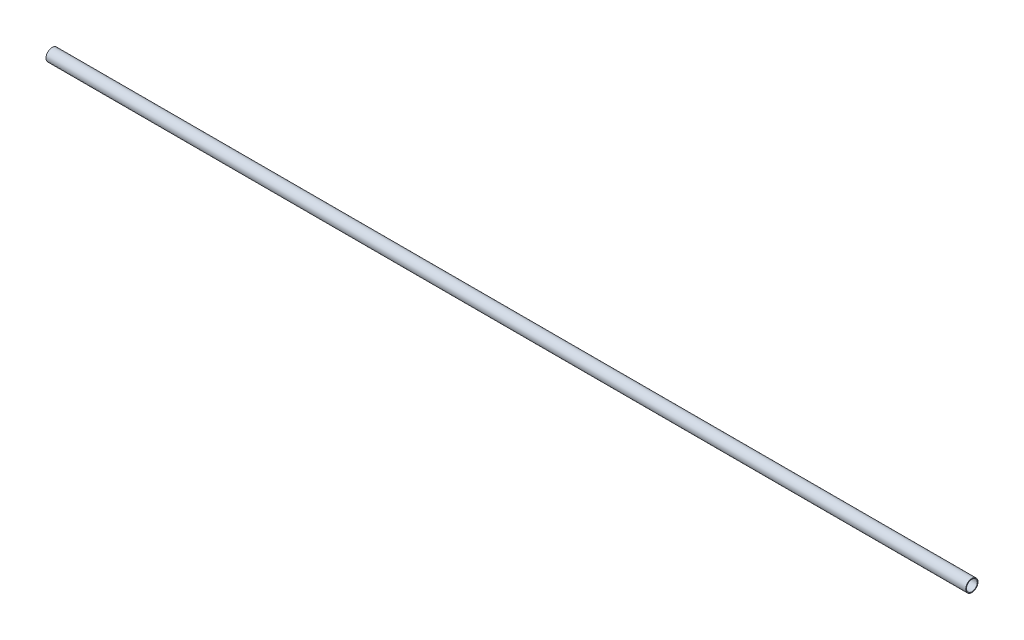
SolidWorks part; units mm, degrees
ref_plane "Front Plane" through (0, 0, 0) normal (0, 0, 1) x (1, 0, 0)
ref_plane "Top Plane" through (0, 0, 0) normal (0, 1, 0) x (1, 0, 0)
ref_plane "Right Plane" through (0, 0, 0) normal (1, 0, 0) x (0, 0, -1)
sketch "Sketch1" plane through (0, 0, 0) normal (1, 0, 0) x (0, 0, -1)
  circle A1 centre (0, 0) radius 11
  circle A2 centre (0, 0) radius 12.5
  dimension "D1" = 1.5
extrude "Boss-Extrude1" add sketch "Sketch1" along normal blind 1872
